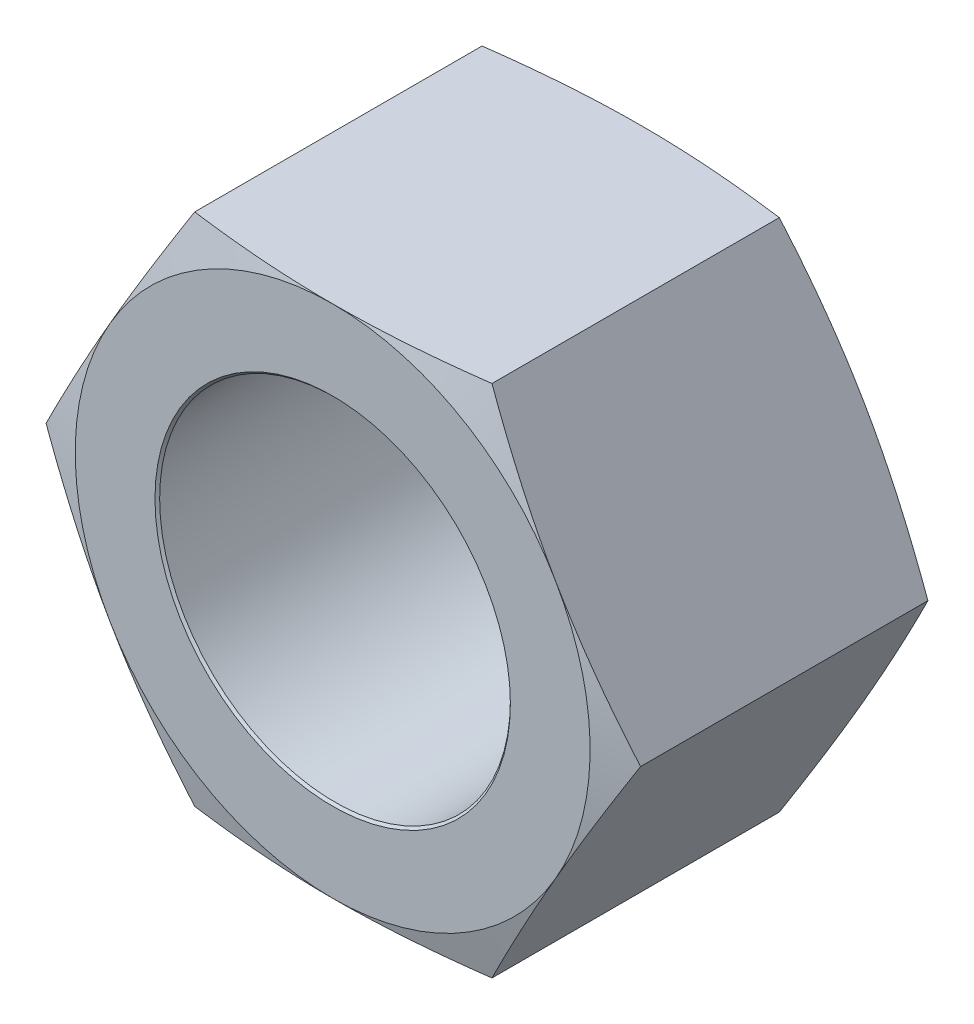
SolidWorks part; units mm, degrees
material "4级"
ref_plane "基准面1" through (0, 0, 0) normal (0, 0, 1) x (1, 0, 0)
ref_plane "基准面2" through (0, 0, 0) normal (0, 1, 0) x (1, 0, 0)
ref_plane "基准面3" through (0, 0, 0) normal (1, 0, 0) x (0, 0, -1)
sketch "尺寸草图" plane through (0, 0, 0) normal (0, 0, 1) x (1, 0, 0)
  line L0 (0, 0) -> (24.1005, 0)
  point P3 (30, 0)
  point P4 (1.5, 0)
  point P5 (50.85, 0)
  point P6 (26.4, 0)
  point P7 (6.4, 0)
  point P8 (46, 0)
  dimension "D" = 30
  dimension "e" = 50.85
  dimension "P1" = 1.5
  dimension "m" = 26.4
  dimension "mw" = 6.4
  dimension "s" = 46
sketch "草图1" plane through (0, 0, 0) normal (0, 0, 1) x (1, 0, 0)
  line L0 (-26.8088, 0) -> (37.1748, 0) construction
  line L1 (0, 25.0215) -> (0, -25.0215) construction
  line L3 (12.7125, 22.0187) -> (-12.7125, 22.0187)
  line L4 (-12.7125, 22.0187) -> (-25.425, 0)
  line L5 (-25.425, 0) -> (-12.7125, -22.0187)
  line L6 (-12.7125, -22.0187) -> (12.7125, -22.0187)
  line L7 (12.7125, -22.0187) -> (25.425, 0)
  line L8 (25.425, 0) -> (12.7125, 22.0187)
  circle A0 centre (0, 0) radius 22.0187 construction
  circle A1 centre (0, 0) radius 15
  dimension "D" = 30
  dimension "e" = 50.85
extrude "基体-拉伸" add sketch "草图1" along normal blind 26.4
cosmetic thread "装饰螺纹线1" parameters "D2"=31.5
sketch "草图2" plane through (0, 0, 0) normal (0, 0, -1) x (-1, 0, 0)
  line L0 (-12.7125, 22.0187) -> (12.7125, 22.0187) construction
  circle A0 centre (0, 0) radius 22.0187
  circle A1 centre (0, 0) radius 15 construction
extrude "切除-拉伸1" cut sketch "草图2" against normal blind 38 draft 75 flip side to cut
sketch "草图3" plane through (0, 0, 26.4) normal (0, 0, 1) x (1, 0, 0)
  line L0 (25.425, 0) -> (12.7125, 22.0187) construction
  circle A0 centre (0, 0) radius 22.0187
extrude "切除-拉伸2" cut sketch "草图3" against normal blind 38 draft 75 flip side to cut
chamfer "倒角1" distance 0.2 angle 45 2 edges at (15, 0, 0) (15, 0, 26.4)
equation "\"e@草图1\" = \"e@尺寸草图\""
equation "\"D@草图1\" = \"D@尺寸草图\""
equation "\"m@基体-拉伸\" = \"m@尺寸草图\""
equation "\"D2@装饰螺纹线1\" = 1.05 * \"D@尺寸草图\""
